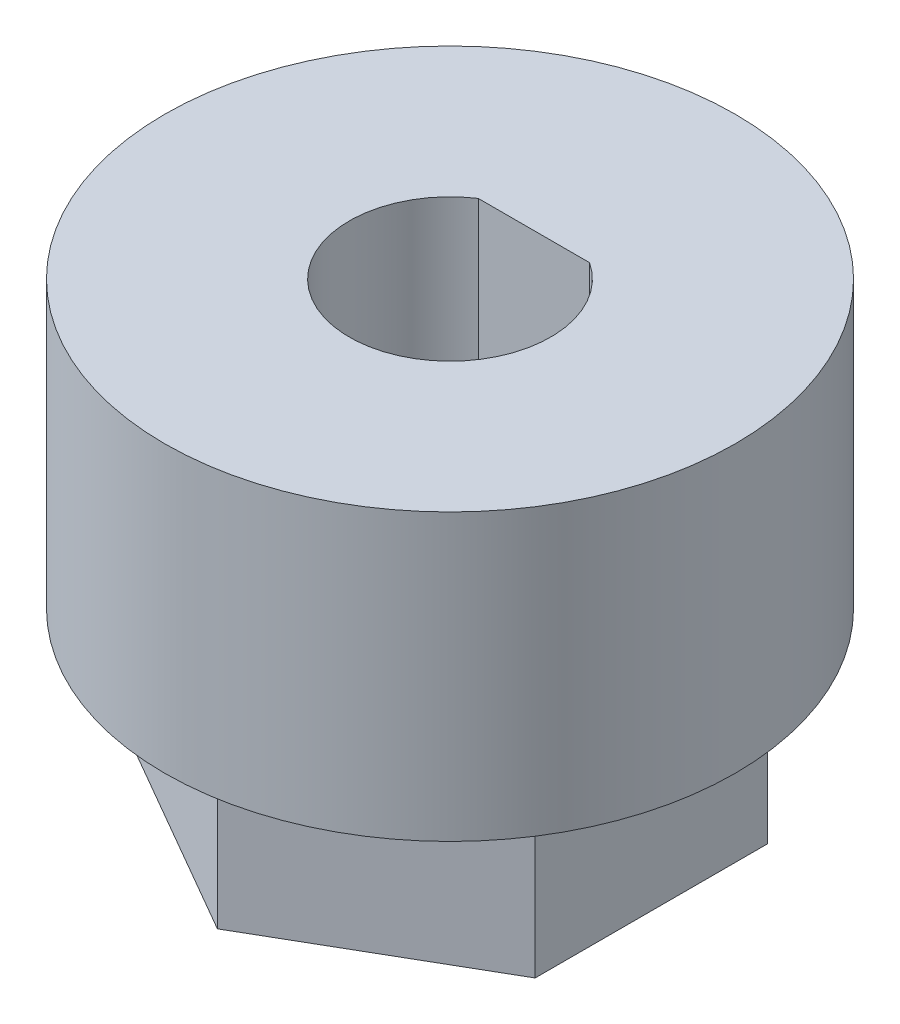
SolidWorks part; units mm, degrees
ref_plane "Front Plane" through (0, 0, 0) normal (0, 0, 1) x (1, 0, 0)
ref_plane "Top Plane" through (0, 0, 0) normal (0, 1, 0) x (1, 0, 0)
ref_plane "Right Plane" through (0, 0, 0) normal (1, 0, 0) x (0, 0, -1)
sketch "Sketch1" plane through (0, 0, 0) normal (0, 1, 0) x (1, 0, 0)
  line L0 (0, 6.9282) -> (0, -6.9282) construction
  line L1 (-6, -3.4641) -> (6, 3.4641) construction
  line L2 (6, -3.4641) -> (-6, 3.4641) construction
  line L3 (-6, 3.4641) -> (0, 6.9282)
  line L4 (0, 6.9282) -> (6, 3.4641)
  line L5 (6, 3.4641) -> (6, -3.4641)
  line L6 (6, -3.4641) -> (0, -6.9282)
  line L7 (0, -6.9282) -> (-6, -3.4641)
  line L8 (-6, -3.4641) -> (-6, 3.4641)
  point P6 (25.0928, 14.4873)
  dimension "D1" = 60
  dimension "D2" = 60
  dimension "D3" = 12
extrude "Boss-Extrude1" add sketch "Sketch1" along normal blind 4.8
sketch "Sketch2" plane through (0, 4.8, 0) normal (0, 1, 0) x (1, 0, 0)
  circle A0 centre (0, 0) radius 8.5
  dimension "D1" = 17
extrude "Boss-Extrude2" add sketch "Sketch2" along normal blind 8.5
sketch "Sketch3" plane through (0, 13.3, 0) normal (0, 1, 0) x (1, 0, 0)
  line L0 (-1.6583, 2.5) -> (1.6583, 2.5)
  line L1 (-3.5908, -3) -> (3.9178, -3) construction
  arc A0 (-1.6583, 2.5) -> (1.6583, 2.5) centre (0, 0) ccw
  dimension "D1" = 3
  dimension "D2" = 5.5
extrude "Cut-Extrude1" cut sketch "Sketch3" against normal through all
